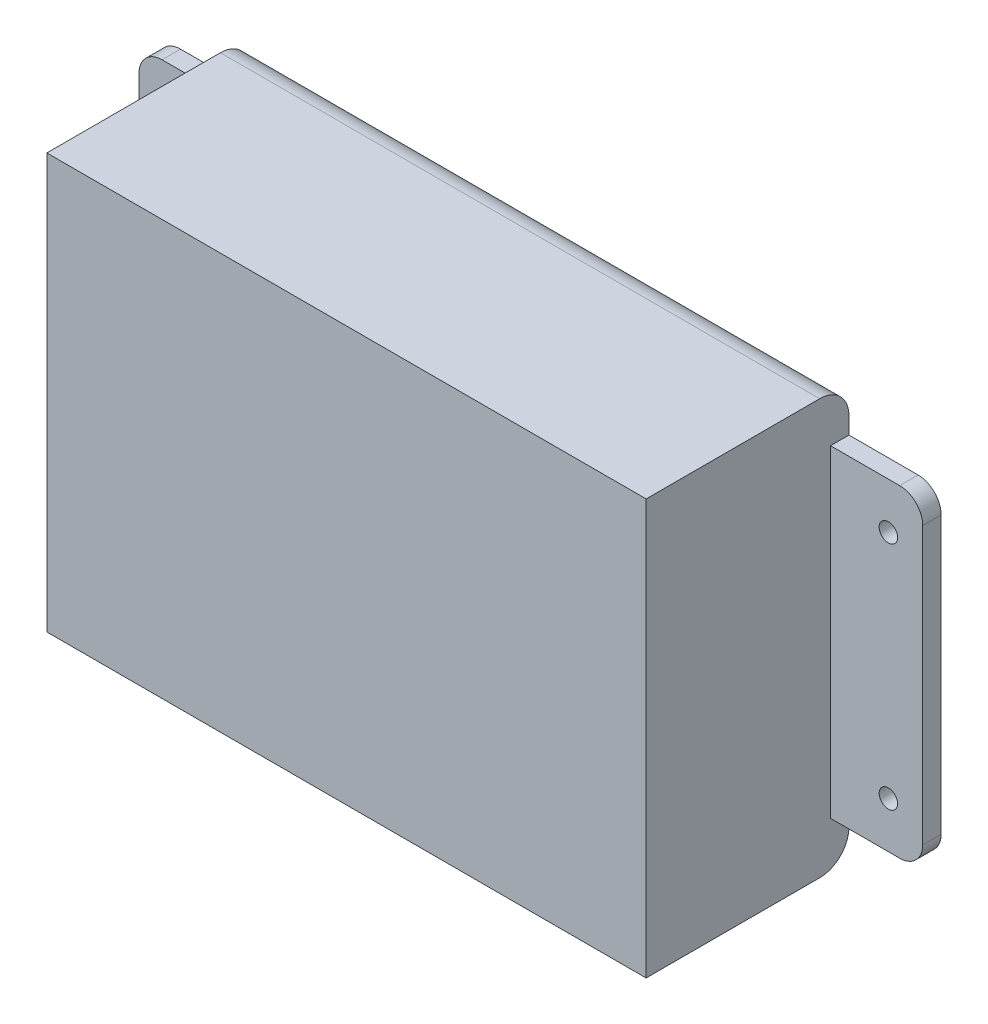
SolidWorks part; units mm, degrees
ref_plane "Front Plane" through (0, 0, 0) normal (0, 0, 1) x (1, 0, 0)
ref_plane "Top Plane" through (0, 0, 0) normal (0, 1, 0) x (1, 0, 0)
ref_plane "Right Plane" through (0, 0, 0) normal (1, 0, 0) x (0, 0, -1)
sketch "Sketch1" plane through (0, 0, 0) normal (0, 0, 1) x (1, 0, 0)
  line L1 (0, 0) -> (170, 0)
  line L2 (0, 0) -> (0, -90)
  line L3 (0, -90) -> (170, -90)
  line L4 (170, 0) -> (170, -90)
  dimension "D1" = 170
  dimension "D2" = 90
extrude "Boss-Extrude1" add sketch "Sketch1" along normal blind 44
fillet "Fillet1" radius 6.35 2 edges at (85, -90, 0) (85, 0, 0)
sketch "Sketch3" plane through (0, 0, 44) normal (0, 0, 1) x (1, 0, 0)
  line L10 (170, 0) -> (0, 0) construction
  line L11 (150, 0) -> (170, 0)
  line L12 (150, 0) -> (150, -90)
  line L13 (150, -90) -> (170, -90)
  line L14 (170, 0) -> (170, -90)
  line L15 (0, -90) -> (170, -90) construction
  line L16 (0, 0) -> (20, 0)
  line L17 (0, 0) -> (0, -90)
  line L18 (0, -90) -> (20, -90)
  line L19 (20, 0) -> (20, -90)
  dimension "D1" = 90
  dimension "D2" = 20
  dimension "D3" = 90
  dimension "D4" = 20
extrude "Cut-Extrude7" cut sketch "Sketch3" against normal blind 40
sketch "Sketch5" plane through (0, 0, 4) normal (0, 0, 1) x (1, 0, 0)
  line L0 (20, -89.5492) -> (20, -0.4508) construction
  line L1 (0, 0) -> (20, 0)
  line L2 (0, 0) -> (0, -10)
  line L3 (0, -10) -> (20, -10)
  line L4 (20, 0) -> (20, -10)
  line L5 (0, -0.4508) -> (0, -89.5492) construction
  line L6 (0, -80) -> (20, -80)
  line L7 (0, -80) -> (0, -90)
  line L8 (0, -90) -> (20, -90)
  line L9 (20, -80) -> (20, -90)
  line L10 (0, -90) -> (20, -90) construction
  line L11 (170, -89.5492) -> (170, -0.4508) construction
  line L12 (150, 0) -> (170, 0)
  line L13 (150, 0) -> (150, -10)
  line L14 (150, -10) -> (170, -10)
  line L15 (170, 0) -> (170, -10)
  line L16 (150, 0) -> (150, -90) construction
  line L17 (150, -80) -> (171.1019, -80)
  line L18 (150, -80) -> (150, -90)
  line L19 (150, -90) -> (171.1019, -90)
  line L20 (171.1019, -80) -> (171.1019, -90)
  dimension "D1" = 10
  dimension "D2" = 10
  dimension "D3" = 10
  dimension "D4" = 10
  dimension "D5" = 20
extrude "Cut-Extrude8" cut sketch "Sketch5" against normal blind 36
sketch "Sketch6" plane through (0, 0, 0) normal (0, 0, -1) x (-1, 0, 0)
  line L0 (0, -10) -> (-20, -10) construction
  line L1 (-20, -80) -> (0, -80) construction
  line L2 (-150, -10) -> (-170, -10) construction
  line L3 (-170, -80) -> (-150, -80) construction
  circle A0 centre (-162.5523, -20) radius 2
  circle A1 centre (-162.5523, -70) radius 2
  circle A2 centre (-10.5035, -20) radius 2
  circle A3 centre (-10.5035, -70) radius 2
  dimension "D1" = 4
  dimension "D2" = 4
  dimension "D3" = 4
  dimension "D4" = 4
  dimension "D5" = 10
  dimension "D6" = 10
  dimension "D7" = 50
  dimension "D8" = 10
  dimension "D9" = 10
  dimension "D10" = 50
extrude "Cut-Extrude9" cut sketch "Sketch6" against normal blind 36
fillet "Fillet3" radius 5 4 edges at (0, -10, 2) (0, -80, 2) (170, -80, 2) (170, -10, 2)
sketch "Sketch7" plane through (0, 0, 0) normal (0, 0, -1) x (-1, 0, 0)
  text T0 "ESC\r\n" font "Constantia" height in points 48
extrude "Cut-Extrude10" cut sketch "Sketch7" against normal blind 10
